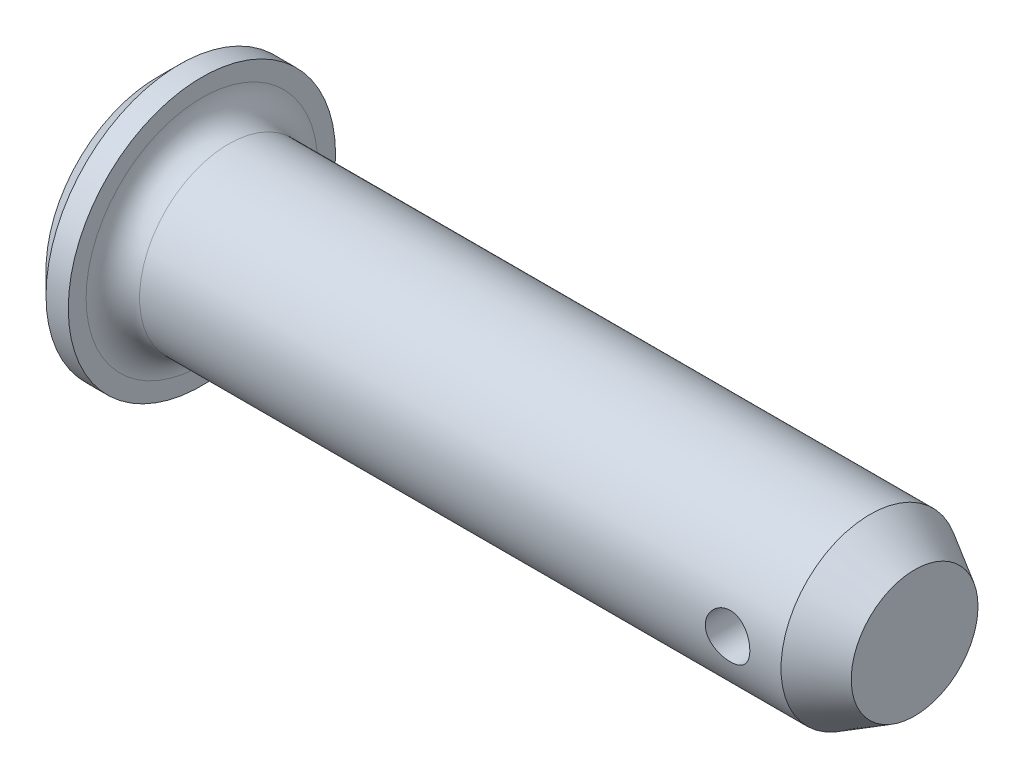
SolidWorks part; units mm, degrees
ref_plane "前视" through (0, 0, 0) normal (0, 0, 1) x (1, 0, 0)
ref_plane "上视" through (0, 0, 0) normal (0, 1, 0) x (1, 0, 0)
ref_plane "右视" through (0, 0, 0) normal (1, 0, 0) x (0, 0, -1)
sketch "尺寸草图" plane through (0, 0, 0) normal (0, 0, 1) x (1, 0, 0)
  line L0 (0, 6) -> (0, 0)
  line L1 (0, 0) -> (16, 0)
  circle A0 centre (13.8, 0) radius 0.5 construction
  point P3 (0, 4)
  point P5 (1, 0)
  point P6 (0.6, 0)
  point P7 (15, 0)
  point P8 (1.5, 0)
  dimension "d1" = 1
  dimension "l" = 16
  dimension "dk" = 6
  dimension "d" = 4
  dimension "k" = 1
  dimension "r" = 0.6
  dimension "c" = 1
  dimension "e" = 0.5
  dimension "le" = 2.2
sketch "草图1" plane through (0, 0, 0) normal (0, 0, 1) x (1, 0, 0)
  line L0 (0, 0) -> (-7.3443, 0) construction
  line L1 (0, 0) -> (17, 0)
  line L2 (0, 0) -> (0, 2.5)
  line L3 (0.5, 3) -> (1, 3)
  line L4 (1, 3) -> (1, 2)
  line L5 (1, 2) -> (17, 2)
  line L6 (17, 2) -> (17, 0)
  line L7 (0, 2.5) -> (0.5, 3)
  point P4 (0, 3)
  dimension "D2" = 6
  dimension "D1" = 16
  dimension "D3" = 4
  dimension "D4" = 1
revolve "基体-旋转" add sketch "草图1" angle 360 about L0
sketch "草图2" plane through (0, 0, 0) normal (0, 0, 1) x (1, 0, 0)
  line L0 (0, 0) -> (16, 0) construction
  line L1 (17, -2) -> (17, 2) construction
  circle A1 centre (14.8, 0) radius 0.5
  dimension "D1" = 1
  dimension "D2" = 2.2
extrude "切除-拉伸1" cut sketch "草图2" against normal through all and the other way through all
fillet "圆角1" radius 0.6 1 edges at (1, 0, -2)
chamfer "倒角1" distance 1 angle 30 1 edges at (17, 0, -2)
